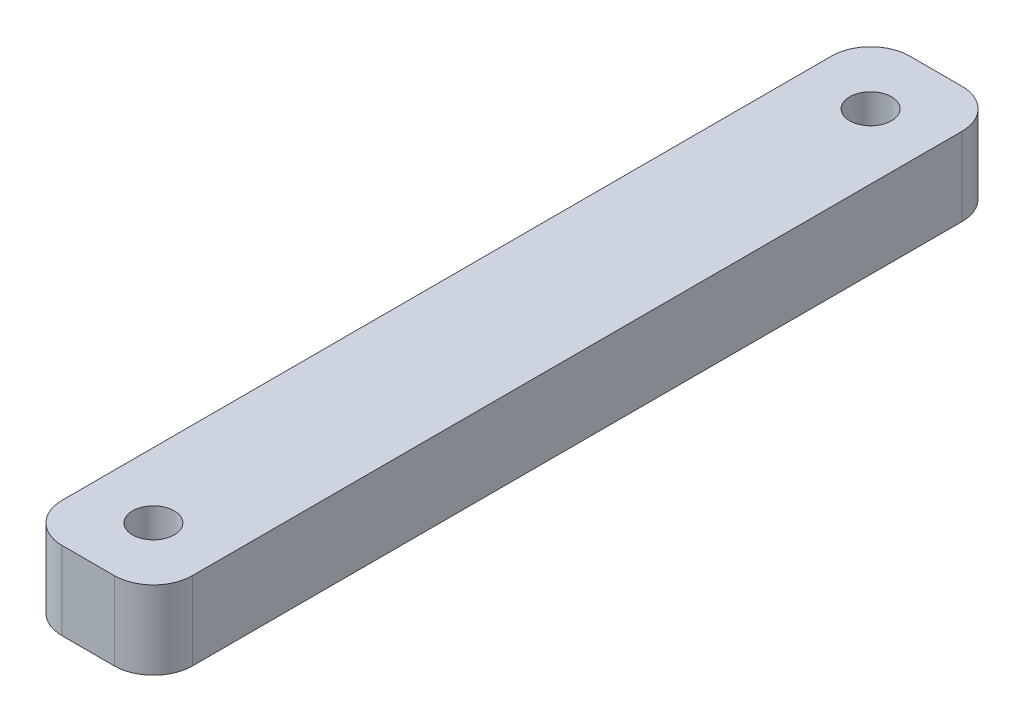
SolidWorks part; units mm, degrees
ref_plane "Front" through (0, 0, 0) normal (0, 0, 1) x (1, 0, 0)
ref_plane "Top" through (0, 0, 0) normal (0, 1, 0) x (1, 0, 0)
ref_plane "Right" through (0, 0, 0) normal (1, 0, 0) x (0, 0, -1)
sketch "Sketch1" plane through (0, 0, 0) normal (0, 0, 1) x (1, 0, 0)
  line L1 (0, 0) -> (10, 0)
  line L2 (0, 0) -> (0, -6)
  line L3 (0, -6) -> (10, -6)
  line L4 (10, 0) -> (10, -6)
  dimension "D1" = 6
  dimension "D2" = 10
extrude "Boss-Extrude1" add sketch "Sketch1" along normal blind 65
sketch "Sketch2" plane through (0, 0, 0) normal (0, 1, 0) x (1, 0, 0)
  line L0 (10, -65) -> (0, -65) construction
  line L1 (10, -65) -> (10, 0) construction
  line L2 (10, 0) -> (0, 0) construction
  circle A0 centre (5, -5) radius 1.6
  circle A1 centre (5, -60) radius 1.6
  dimension "D1" = 3.2
  dimension "D2" = 3.2
  dimension "D3" = 5
  dimension "D4" = 5
  dimension "D5" = 5
  dimension "D6" = 5
extrude "Cut-Extrude1" cut sketch "Sketch2" against normal through all
fillet "Fillet1" radius 3 4 edges at (0, -3, 0) (10, -3, 0) (0, -3, 65) (10, -3, 65)
